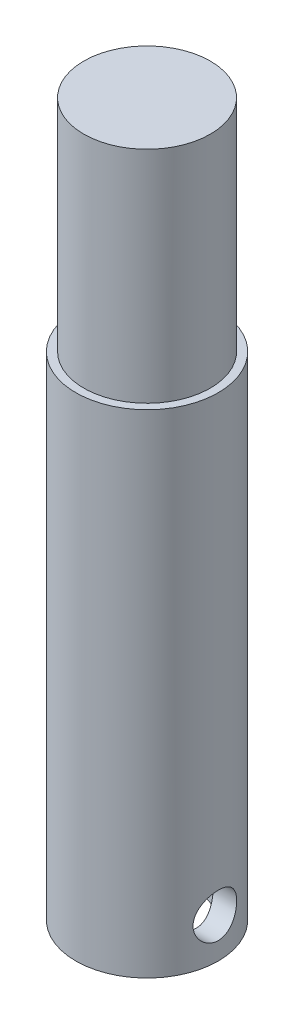
SolidWorks part; units mm, degrees
ref_plane "Front Plane" through (0, 0, 0) normal (0, 0, 1) x (1, 0, 0)
ref_plane "Top Plane" through (0, 0, 0) normal (0, 1, 0) x (1, 0, 0)
ref_plane "Right Plane" through (0, 0, 0) normal (1, 0, 0) x (0, 0, -1)
sketch "Sketch1" plane through (0, 0, 0) normal (0, 1, 0) x (1, 0, 0)
  line L0 (-4.0996, 3) -> (4.0996, 3)
  arc A0 (-4.0996, 3) -> (4.0996, 3) centre (0, 0) ccw
  dimension "D1" = 10.16
  dimension "D2" = 3
extrude "Boss-Extrude1" add sketch "Sketch1" along normal blind 57.15
sketch "Sketch3" plane through (0, 0, 0) normal (0, -1, 0) x (1, 0, 0)
  line L0 (-4.0996, -3) -> (4.0996, -3)
  arc A0 (-4.0996, -3) -> (4.0996, -3) centre (0, 0) ccw
extrude "Boss-Extrude2" add sketch "Sketch3" against normal up to surface (57.15 mm away) up to face at (0, 57.15, 1.04)
sketch "Sketch4" plane through (0, 57.15, 0) normal (0, 1, 0) x (1, 0, 0)
  line L1 (-4.0996, 3) -> (4.0996, 3)
  arc A0 (-4.0996, 3) -> (4.0996, 3) centre (0, 0) cw
extrude "Boss-Extrude3" add sketch "Sketch4" against normal blind 6.35
sketch "Sketch5" plane through (0, 0, 0) normal (0, -1, 0) x (1, 0, 0)
  circle A0 centre (0, 0) radius 3.9688
  dimension "D1" = 7.9375
extrude "Cut-Extrude1" cut sketch "Sketch5" against normal blind 6.35
ref_plane "Plane1" through (5.08, 0, 0) normal (1, 0, 0) x (0, 0, -1)
ref_plane "Plane2" through (0, 6.35, 0) normal (0, -1, 0) x (-1, 0, 0)
sketch "Sketch7" plane through (0, 6.35, 0) normal (0, -1, 0) x (-1, 0, 0)
  circle A0 centre (0, 0) radius 5.715
  circle A1 centre (0, 0) radius 3.9688
  dimension "D1" = 11.43
extrude "Boss-Extrude4" add sketch "Sketch7" along normal up to surface (6.35 mm away) and the other way blind 33.147 contours A0
sketch "Sketch6" plane through (5.08, 0, 0) normal (1, 0, 0) x (0, 0, -1)
  circle A0 centre (0, 3.175) radius 1.75
  dimension "D1" = 3.5
  dimension "D2" = 3.175
extrude "Cut-Extrude2" cut sketch "Sketch6" against normal through all both and the other way through all
